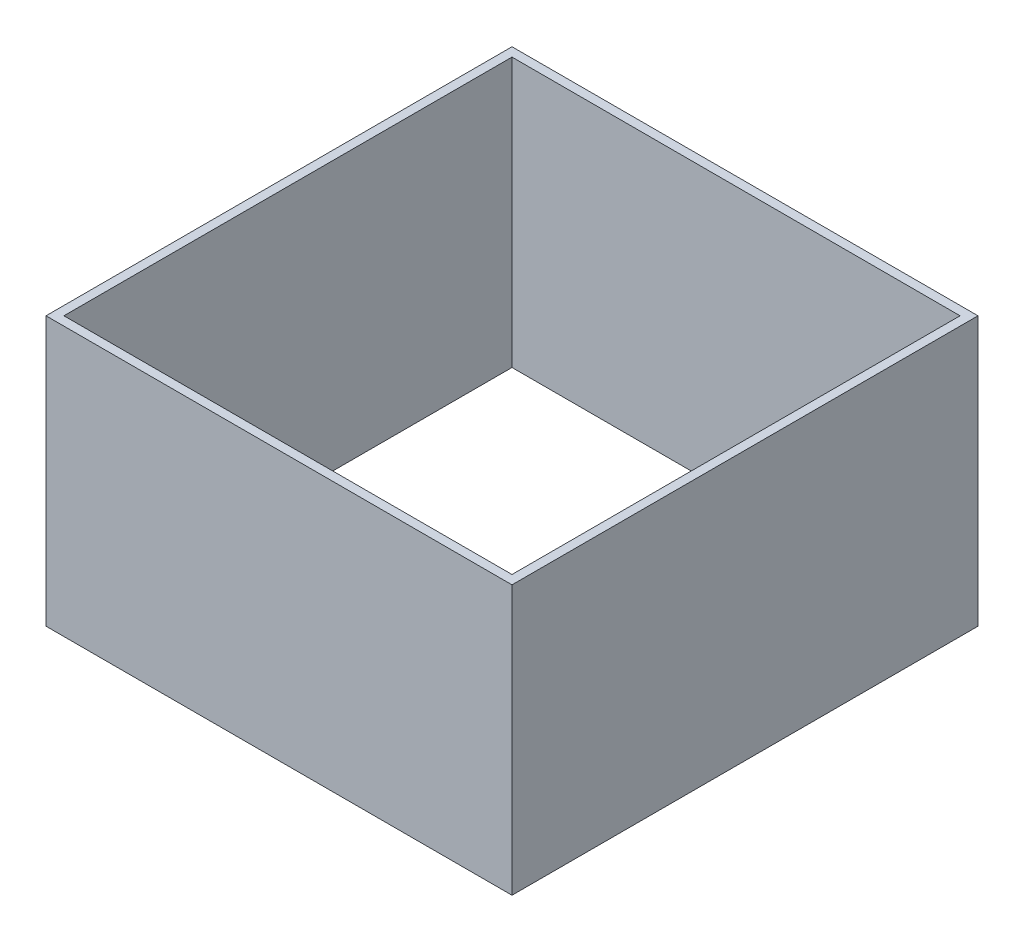
SolidWorks part; units mm, degrees
ref_plane "Front Plane" through (0, 0, 0) normal (0, 0, 1) x (1, 0, 0)
ref_plane "Top Plane" through (0, 0, 0) normal (0, 1, 0) x (1, 0, 0)
ref_plane "Right Plane" through (0, 0, 0) normal (1, 0, 0) x (0, 0, -1)
sketch "Sketch1" plane through (0, 0, 0) normal (0, 1, 0) x (1, 0, 0)
  line L0 (1, 1) -> (51, 1)
  line L1 (0, 0) -> (52, 0)
  line L2 (0, 0) -> (0, 52)
  line L3 (0, 52) -> (52, 52)
  line L4 (52, 0) -> (52, 52)
  line L9 (51, 1) -> (51, 51)
  line L10 (1, 51) -> (51, 51)
  line L11 (1, 1) -> (1, 51)
  dimension "D1" = 52
  dimension "D2" = 52
  dimension "D3" = 1
extrude "Boss-Extrude1" add sketch "Sketch1" along normal blind 30
